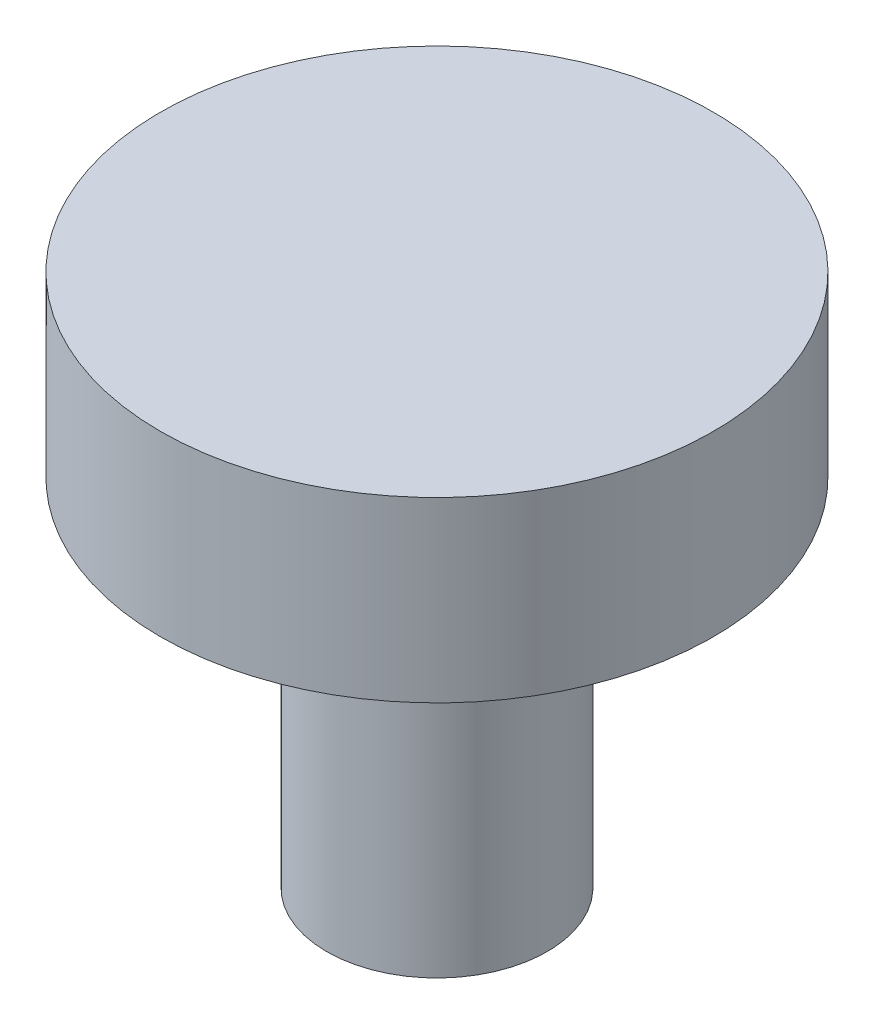
SolidWorks part; units mm, degrees
ref_plane "Front Plane" through (0, 0, 0) normal (0, 0, 1) x (1, 0, 0)
ref_plane "Top Plane" through (0, 0, 0) normal (0, 1, 0) x (1, 0, 0)
ref_plane "Right Plane" through (0, 0, 0) normal (1, 0, 0) x (0, 0, -1)
sketch "Sketch1" plane through (0, 0, 0) normal (0, 1, 0) x (1, 0, 0)
  circle A0 centre (0, 0) radius 15.748
  dimension "D1" = 31.496
extrude "Boss-Extrude1" add sketch "Sketch1" along normal blind 50.8
sketch "Sketch2" plane through (0, 50.8, 0) normal (0, 1, 0) x (1, 0, 0)
  circle A0 centre (0, 0) radius 39.481
extrude "Boss-Extrude2" add sketch "Sketch2" along normal blind 25.4
